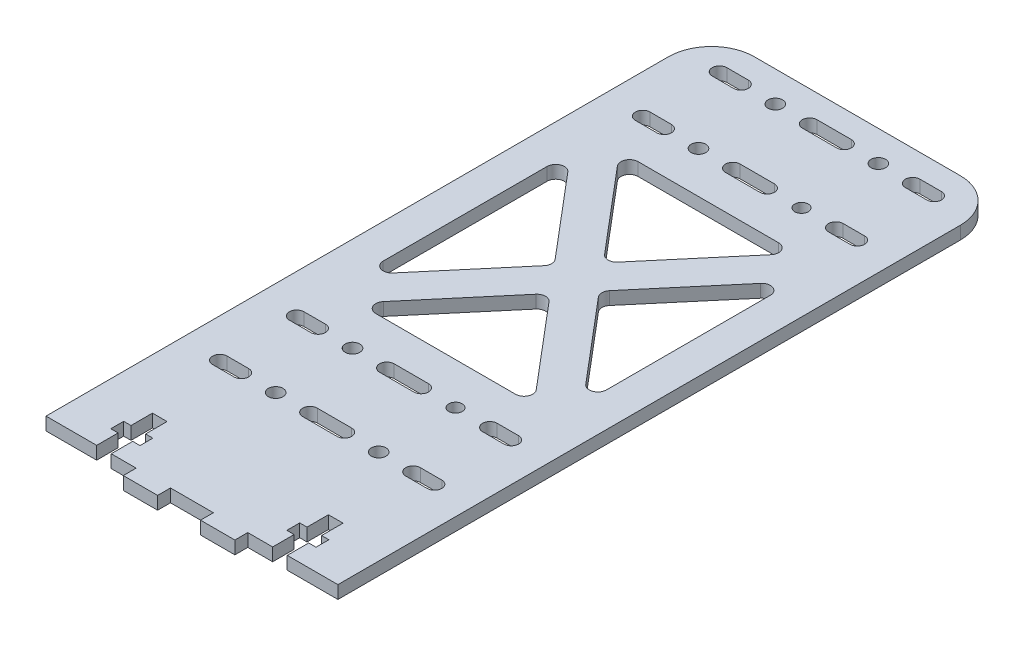
SolidWorks part; units mm, degrees
material "Thornel Mat VMA"
ref_plane "前视基准面" through (0, 0, 0) normal (0, 0, 1) x (1, 0, 0)
ref_plane "上视基准面" through (0, 0, 0) normal (0, 1, 0) x (1, 0, 0)
ref_plane "右视基准面" through (0, 0, 0) normal (1, 0, 0) x (0, 0, -1)
sketch "草图1" plane through (0, 0, 0) normal (0, 1, 0) x (1, 0, 0)
  line L0 (0, 0) -> (7.8, 0)
  line L1 (60, 0) -> (60, 150)
  line L2 (60, 150) -> (0, 150)
  line L3 (0, 150) -> (0, 0)
  line L4 (17, 0) -> (17, -3)
  line L5 (17, -3) -> (25, -3)
  line L6 (25, -3) -> (25, 0)
  line L7 (35, 0) -> (35, -3)
  line L8 (35, -3) -> (43, -3)
  line L9 (43, -3) -> (43, 0)
  line L21 (25, 0) -> (31.7, 0)
  line L22 (31.7, 0) -> (35, 0)
  line L23 (43, 0) -> (48.8, 0)
  line L24 (7.8, 0) -> (7.8, 5)
  line L25 (7.8, 5) -> (6.1, 5)
  line L26 (6.1, 5) -> (6.1, 8)
  line L27 (6.1, 8) -> (7.8, 8)
  line L28 (7.8, 8) -> (7.8, 13)
  line L29 (7.8, 13) -> (11.2, 13)
  line L30 (11.2, 13) -> (11.2, 8)
  line L31 (11.2, 8) -> (12.9, 8)
  line L32 (12.9, 8) -> (12.9, 5)
  line L33 (12.9, 5) -> (11.2, 5)
  line L34 (11.2, 5) -> (11.2, 0)
  line L35 (30, 5) -> (30, 15.2724) construction
  line L36 (48.8, 5) -> (48.8, 0)
  line L37 (47.1, 5) -> (48.8, 5)
  line L38 (52.2, 0) -> (52.2, 5)
  line L39 (52.2, 5) -> (53.9, 5)
  line L40 (53.9, 5) -> (53.9, 8)
  line L41 (53.9, 8) -> (52.2, 8)
  line L42 (48.8, 8) -> (47.1, 8)
  line L43 (47.1, 8) -> (47.1, 5)
  line L44 (52.2, 8) -> (52.2, 13)
  line L45 (48.8, 13) -> (48.8, 8)
  line L46 (52.2, 13) -> (48.8, 13)
  line L47 (11.2, 0) -> (17, 0)
  line L48 (52.2, 0) -> (60, 0)
  dimension "D1" = 60
  dimension "D2" = 8
  dimension "D3" = 8
  dimension "D4" = 3
  dimension "D5" = 10
  dimension "D6" = 3
  dimension "D7" = 17
  dimension "D8" = 5
  dimension "D9" = 5
  dimension "D10" = 1.7
  dimension "D11" = 1.7
  dimension "D12" = 3
  dimension "D13" = 3
  dimension "D14" = 5
  dimension "D15" = 3.4
  dimension "D16" = 3.4
  dimension "D17" = 0
  dimension "D18" = 7.8
  dimension "D19" = 150
  dimension "D20" = 30
extrude "凸台-拉伸1" add sketch "草图1" along normal blind 3
sketch "草图2" plane through (0, 3, 0) normal (0, 1, 0) x (1, 0, 0)
  line L0 (60, 0) -> (60, 150) construction
  line L1 (60, 150) -> (0, 150) construction
  line L2 (5, 130) -> (10, 130) construction
  line L3 (5, 131.7) -> (10, 131.7)
  line L4 (5, 128.3) -> (10, 128.3)
  line L5 (26, 130) -> (34, 130) construction
  line L6 (26, 131.7) -> (34, 131.7)
  line L7 (26, 128.3) -> (34, 128.3)
  line L8 (50, 130) -> (55, 130) construction
  line L9 (50, 131.7) -> (55, 131.7)
  line L10 (50, 128.3) -> (55, 128.3)
  line L11 (5, 147.9) -> (10, 147.9) construction
  line L12 (5, 149.6) -> (10, 149.6)
  line L13 (5, 146.2) -> (10, 146.2)
  line L14 (26, 147.9) -> (34, 147.9) construction
  line L15 (26, 149.6) -> (34, 149.6)
  line L16 (26, 146.2) -> (34, 146.2)
  line L17 (50, 147.9) -> (55, 147.9) construction
  line L18 (50, 149.6) -> (55, 149.6)
  line L19 (50, 146.2) -> (55, 146.2)
  line L20 (0, 150) -> (0, 0) construction
  line L21 (-15.6289, 89.7) -> (77.6031, 89.7) construction
  line L22 (5, 49.4) -> (10, 49.4) construction
  line L23 (5, 47.7) -> (10, 47.7)
  line L24 (5, 51.1) -> (10, 51.1)
  line L25 (26, 49.4) -> (34, 49.4) construction
  line L26 (26, 47.7) -> (34, 47.7)
  line L27 (26, 51.1) -> (34, 51.1)
  line L28 (50, 49.4) -> (55, 49.4) construction
  line L29 (50, 47.7) -> (55, 47.7)
  line L30 (50, 51.1) -> (55, 51.1)
  line L31 (5, 31.5) -> (10, 31.5) construction
  line L32 (5, 29.8) -> (10, 29.8)
  line L33 (5, 33.2) -> (10, 33.2)
  line L34 (26, 31.5) -> (34, 31.5) construction
  line L35 (26, 29.8) -> (34, 29.8)
  line L36 (26, 33.2) -> (34, 33.2)
  line L37 (50, 31.5) -> (55, 31.5) construction
  line L38 (50, 29.8) -> (55, 29.8)
  line L39 (50, 33.2) -> (55, 33.2)
  line L40 (25, 0) -> (35, 0) construction
  circle A0 centre (18, 130) radius 1.7
  circle A1 centre (42, 130) radius 1.57
  arc A2 (5, 131.7) -> (5, 128.3) centre (5, 130) ccw
  arc A3 (10, 128.3) -> (10, 131.7) centre (10, 130) ccw
  arc A4 (26, 131.7) -> (26, 128.3) centre (26, 130) ccw
  arc A5 (34, 128.3) -> (34, 131.7) centre (34, 130) ccw
  arc A6 (50, 131.7) -> (50, 128.3) centre (50, 130) ccw
  arc A7 (55, 128.3) -> (55, 131.7) centre (55, 130) ccw
  arc A8 (5, 149.6) -> (5, 146.2) centre (5, 147.9) ccw
  arc A9 (10, 146.2) -> (10, 149.6) centre (10, 147.9) ccw
  arc A10 (26, 149.6) -> (26, 146.2) centre (26, 147.9) ccw
  arc A11 (34, 146.2) -> (34, 149.6) centre (34, 147.9) ccw
  arc A12 (50, 149.6) -> (50, 146.2) centre (50, 147.9) ccw
  arc A13 (55, 146.2) -> (55, 149.6) centre (55, 147.9) ccw
  circle A14 centre (18, 147.9) radius 1.7
  circle A15 centre (42, 147.9) radius 1.7
  arc A16 (5, 47.7) -> (5, 51.1) centre (5, 49.4) cw
  arc A17 (10, 51.1) -> (10, 47.7) centre (10, 49.4) cw
  arc A18 (26, 47.7) -> (26, 51.1) centre (26, 49.4) cw
  arc A19 (34, 51.1) -> (34, 47.7) centre (34, 49.4) cw
  arc A20 (50, 47.7) -> (50, 51.1) centre (50, 49.4) cw
  arc A21 (55, 51.1) -> (55, 47.7) centre (55, 49.4) cw
  arc A22 (5, 29.8) -> (5, 33.2) centre (5, 31.5) cw
  arc A23 (10, 33.2) -> (10, 29.8) centre (10, 31.5) cw
  arc A24 (26, 29.8) -> (26, 33.2) centre (26, 31.5) cw
  arc A25 (34, 33.2) -> (34, 29.8) centre (34, 31.5) cw
  arc A26 (50, 29.8) -> (50, 33.2) centre (50, 31.5) cw
  arc A27 (55, 33.2) -> (55, 29.8) centre (55, 31.5) cw
  circle A28 centre (42, 31.5) radius 1.7
  circle A29 centre (18, 31.5) radius 1.7
  circle A30 centre (42, 49.4) radius 1.57
  circle A31 centre (18, 49.4) radius 1.7
  point P10 (7.5, 130)
  point P15 (30, 130)
  point P22 (52.5, 130)
  point P31 (7.5, 147.9)
  point P36 (30, 147.9)
  point P43 (52.5, 147.9)
  point P60 (7.5, 49.4)
  point P67 (30, 49.4)
  point P74 (52.5, 49.4)
  point P81 (7.5, 31.5)
  point P88 (30, 31.5)
  point P95 (52.5, 31.5)
  dimension "D1" = 3.4
  dimension "D2" = 3.14
  dimension "D3" = 24
  dimension "D4" = 18
  dimension "D5" = 20
  dimension "D6" = 20
  dimension "D8" = 8
  dimension "D9" = 1.7
  dimension "D10" = 1.7
  dimension "D11" = 8
  dimension "D14" = 1.7
  dimension "D15" = 8
  dimension "D16" = 3.4
  dimension "D17" = 3.4
  dimension "D18" = 1.7
  dimension "D19" = 1.7
  dimension "D20" = 1.7
  dimension "D22" = 0
  dimension "D23" = 0
  dimension "D24" = 18
  dimension "D25" = 18
  dimension "D29" = 5
  dimension "D30" = 8
  dimension "D31" = 8
  dimension "D7" = 8
  dimension "D12" = 5
  dimension "D13" = 5
  dimension "D21" = 14.5
  dimension "D26" = 8
  dimension "D27" = 5
  dimension "D28" = 5
  dimension "D32" = 29.8
extrude "切除-拉伸1" cut sketch "草图2" against normal blind 3
sketch "草图3" plane through (0, 0, -150) normal (0, 0, -1) x (-1, 0, 0)
  line L4 (-60, 0) -> (0, 0)
  line L5 (0, 0) -> (0, 3)
  line L6 (0, 3) -> (-60, 3)
  line L7 (-60, 3) -> (-60, 0)
  line L8 (-60, 0) -> (0, 0)
  line L9 (0, 0) -> (0, 3)
  line L10 (0, 3) -> (-60, 3)
  line L11 (-60, 3) -> (-60, 0)
  dimension "D1" = 0
extrude "凸台-拉伸2" add sketch "草图3" along normal blind 5
sketch "草图6" plane through (60, 0, 0) normal (1, 0, 0) x (0, 0, -1)
  line L4 (0, 0) -> (155, 0)
  line L5 (155, 0) -> (155, 3)
  line L6 (155, 3) -> (0, 3)
  line L7 (0, 3) -> (0, 0)
  line L8 (0, 0) -> (155, 0)
  line L9 (155, 0) -> (155, 3)
  line L10 (155, 3) -> (0, 3)
  line L11 (0, 3) -> (0, 0)
  dimension "D1" = 0
extrude "凸台-拉伸3" add sketch "草图6" along normal blind 4
sketch "草图7" plane through (0, 0, 0) normal (-1, 0, 0) x (0, 0, 1)
  line L8 (-155, 0) -> (0, 0)
  line L9 (0, 0) -> (0, 3)
  line L10 (0, 3) -> (-155, 3)
  line L11 (-155, 3) -> (-155, 0)
  line L12 (-155, 0) -> (0, 0)
  line L13 (0, 0) -> (0, 3)
  line L14 (0, 3) -> (-155, 3)
  line L15 (-155, 3) -> (-155, 0)
  dimension "D1" = 0
extrude "凸台-拉伸4" add sketch "草图7" along normal blind 4
fillet "圆角1" radius 10 2 edges at (-4, 1.5, -155) (64, 1.5, -155)
sketch "草图9" plane through (0, 3, 0) normal (0, 1, 0) x (1, 0, 0)
  line L0 (26, 128.3) -> (34, 128.3) construction
  line L1 (9.3227, 120.3) -> (50.6773, 120.3)
  line L2 (4, 114.2048) -> (4, 65.0952)
  line L3 (9.4073, 59.1) -> (50.5927, 59.1)
  line L4 (56, 114.2048) -> (56, 65.0952)
  line L5 (30, 89.65) -> (32.6191, 86.5524) construction
  line L6 (27.3809, 86.5524) -> (30, 89.65) construction
  line L7 (64, 145) -> (64, 0) construction
  line L8 (-4, 0) -> (-4, 145) construction
  line L9 (34, 51.1) -> (26, 51.1) construction
  line L10 (9.3227, 120.3) -> (30, 95.8452)
  line L11 (50.5927, 59.1) -> (30, 83.4548)
  line L12 (4, 65.0952) -> (24.7618, 89.65)
  line L13 (56, 114.2048) -> (35.2382, 89.65)
  line L14 (35.2382, 89.65) -> (56, 65.0952)
  line L15 (24.7618, 89.65) -> (4, 114.2048)
  line L16 (30, 83.4548) -> (9.4073, 59.1)
  line L17 (30, 95.8452) -> (50.6773, 120.3)
  point P4 (30, 89.65)
  dimension "D1" = 8
  dimension "D2" = 8
  dimension "D3" = 8
  dimension "D4" = 8
  dimension "D5" = 8
  dimension "D6" = 8
  dimension "D7" = 4
  dimension "D8" = 4
extrude "切除-拉伸3" cut sketch "草图9" against normal blind 4
fillet "圆角3" radius 2 12 edges at (56, 1.5, -65.0952) (50.5927, 1.5, -59.1) (4, 1.5, -65.0952) (9.4073, 1.5, -59.1) (30, 1.5, -83.4548) (24.7618, 1.5, -89.65) (4, 1.5, -114.2048) (56, 1.5, -114.2048) (35.2382, 1.5, -89.65) (30, 1.5, -95.8452) (9.3227, 1.5, -120.3) (50.6773, 1.5, -120.3)
